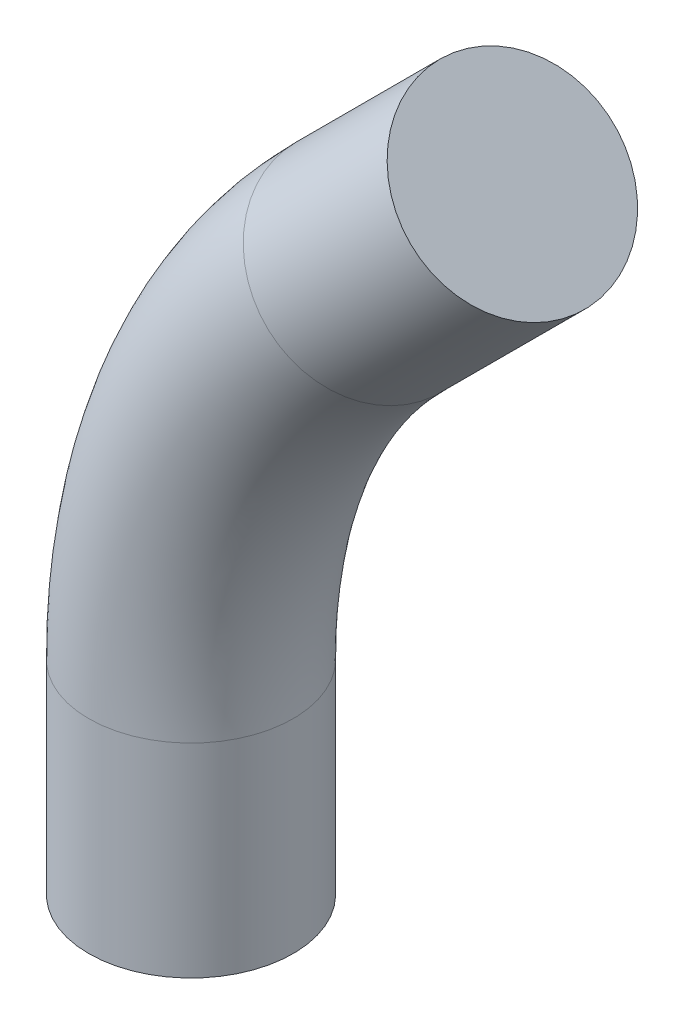
SolidWorks part; units mm, degrees
ref_plane "Front Plane" through (0, 0, 0) normal (0, 0, 1) x (1, 0, 0)
ref_plane "Top Plane" through (0, 0, 0) normal (0, 1, 0) x (1, 0, 0)
ref_plane "Right Plane" through (0, 0, 0) normal (1, 0, 0) x (0, 0, -1)
sketch "Sketch1" plane through (0, 0, 0) normal (0, 0, 1) x (1, 0, 0)
  line L0 (0, 0) -> (0, 13.4315)
  line L1 (11.7157, 41.7157) -> (21.2132, 51.2132)
  arc A0 (0, 13.4315) -> (11.7157, 41.7157) centre (40, 13.4315) cw
  point P6 (0, 30)
  dimension "D3" = 40
  dimension "D1" = 30
  dimension "D2" = 30
  dimension "D4" = 135
sketch "Sketch2" plane through (0, 0, 0) normal (0, 1, 0) x (1, 0, 0)
  circle A0 centre (0, 0) radius 6.75
  dimension "D1" = 13.5
sweep "Sweep1" add profiles "Sketch2" path "Sketch1"
